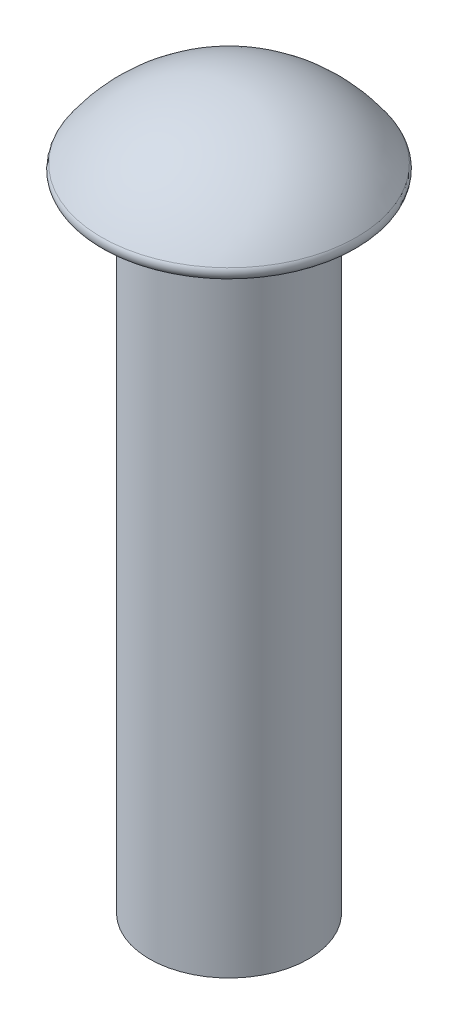
SolidWorks part; units mm, degrees
material "Stainless Steel (ferritic)"
ref_plane "Front Plane" through (0, 0, 0) normal (0, 0, 1) x (1, 0, 0)
ref_plane "Top Plane" through (0, 0, 0) normal (0, 1, 0) x (1, 0, 0)
ref_plane "Right Plane" through (0, 0, 0) normal (1, 0, 0) x (0, 0, -1)
sketch "Sketch1" plane through (0, 0, 0) normal (0, 0, 1) x (1, 0, 0)
  line L0 (0, -4.5) -> (0, 4.5)
  line L1 (0, -4.5) -> (1, -4.5)
  line L2 (1, -4.5) -> (1, 3.5)
  line L3 (1, 3.5) -> (1.7, 3.5)
  arc A1 (1.7, 3.5) -> (0, 4.5) centre (0, 2.555) ccw
  point P10 (0, 0)
  dimension "D1" = 1.7
  dimension "D2" = 1
  dimension "D3" = 8
  dimension "D4" = 1
revolve "Revolve1" add sketch "Sketch1" angle 360 about L0
fillet "Fillet1" radius 0.1 1 edges at (1.7, 3.5, 0)
